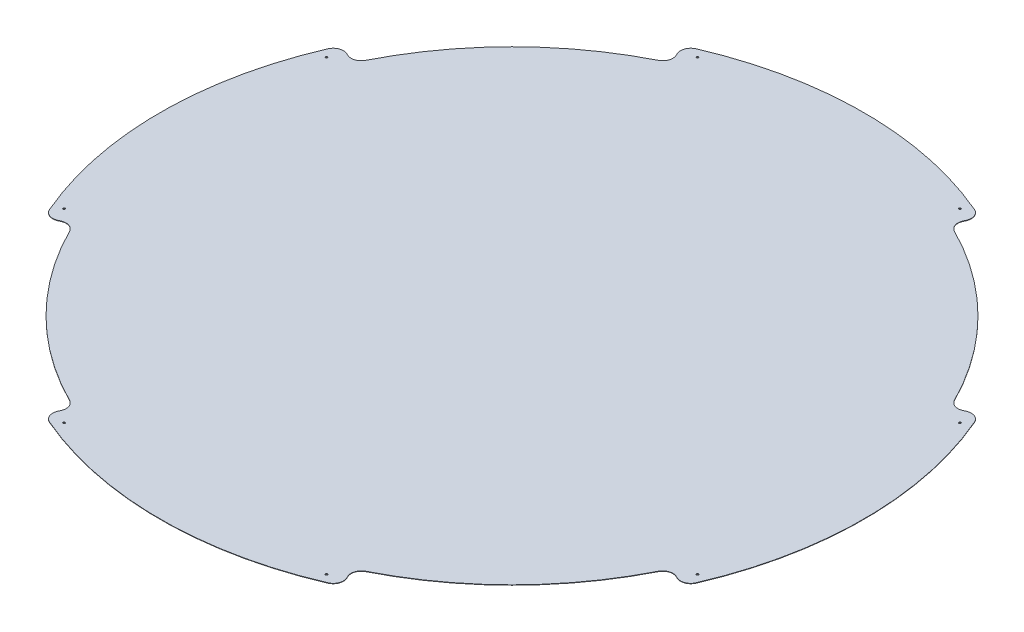
SolidWorks part; units mm, degrees
ref_plane "Front" through (0, 0, 0) normal (0, 0, 1) x (1, 0, 0)
ref_plane "Top" through (0, 0, 0) normal (0, 1, 0) x (1, 0, 0)
ref_plane "Right" through (0, 0, 0) normal (1, 0, 0) x (0, 0, -1)
sketch "Sketch1" plane through (0, 0, 0) normal (0, 1, 0) x (1, 0, 0)
  line L0 (0, 0) -> (0, 168) construction
  line L1 (0, 0) -> (64.2908, 155.2118) construction
  line L2 (0, 0) -> (155.2118, 64.2908) construction
  line L3 (0, 0) -> (155.2118, -64.2908) construction
  line L4 (0, 0) -> (64.2908, -155.2118) construction
  line L5 (0, 0) -> (-64.2908, -155.2118) construction
  line L6 (0, 0) -> (-155.2118, -64.2908) construction
  line L7 (0, 0) -> (-155.2118, 64.2908) construction
  line L8 (0, 0) -> (-64.2908, 155.2118) construction
  line L9 (70.757, 151.7389) -> (70.3342, 150.8322)
  line L10 (-70.757, 151.7389) -> (-70.3342, 150.8322)
  line L11 (151.7389, 70.757) -> (150.8322, 70.3342)
  line L12 (151.7389, -70.757) -> (150.8322, -70.3342)
  line L13 (70.757, -151.7389) -> (70.3342, -150.8322)
  line L14 (-70.757, -151.7389) -> (-70.3342, -150.8322)
  line L15 (-151.7389, -70.757) -> (-150.8322, -70.3342)
  line L16 (-151.7389, 70.757) -> (-150.8322, 70.3342)
  arc A0 (-72.6175, 144.2531) -> (-144.2531, 72.6175) centre (0, 0) ccw
  circle A1 centre (0, 0) radius 168 construction
  arc A2 (-158.4446, 68.2024) -> (-158.4446, -68.2024) centre (0, 0) ccw
  arc A3 (68.2024, 158.4446) -> (-68.2024, 158.4446) centre (0, 0) ccw
  arc A4 (144.2531, 72.6175) -> (72.6175, 144.2531) centre (0, 0) ccw
  arc A5 (158.4446, -68.2024) -> (158.4446, 68.2024) centre (0, 0) ccw
  arc A6 (72.6175, -144.2531) -> (144.2531, -72.6175) centre (0, 0) ccw
  arc A7 (-68.2024, -158.4446) -> (68.2024, -158.4446) centre (0, 0) ccw
  arc A8 (-144.2531, -72.6175) -> (-72.6175, -144.2531) centre (0, 0) ccw
  arc A9 (-151.7389, -70.757) -> (-158.4446, -68.2024) centre (-153.852, -66.2255) cw
  arc A10 (-150.8322, -70.3342) -> (-144.2531, -72.6175) centre (-148.7191, -74.8657) cw
  arc A11 (-70.757, -151.7389) -> (-68.2024, -158.4446) centre (-66.2255, -153.852) ccw
  arc A12 (-70.3342, -150.8322) -> (-72.6175, -144.2531) centre (-74.8657, -148.7191) ccw
  arc A13 (70.757, -151.7389) -> (68.2024, -158.4446) centre (66.2255, -153.852) cw
  arc A14 (70.3342, -150.8322) -> (72.6175, -144.2531) centre (74.8657, -148.7191) cw
  arc A15 (150.8322, -70.3342) -> (144.2531, -72.6175) centre (148.7191, -74.8657) ccw
  arc A16 (151.7389, -70.757) -> (158.4446, -68.2024) centre (153.852, -66.2255) ccw
  arc A17 (151.7389, 70.757) -> (158.4446, 68.2024) centre (153.852, 66.2255) cw
  arc A18 (150.8322, 70.3342) -> (144.2531, 72.6175) centre (148.7191, 74.8657) cw
  arc A19 (-150.8322, 70.3342) -> (-144.2531, 72.6175) centre (-148.7191, 74.8657) ccw
  arc A20 (-151.7389, 70.757) -> (-158.4446, 68.2024) centre (-153.852, 66.2255) ccw
  arc A21 (70.3342, 150.8322) -> (72.6175, 144.2531) centre (74.8657, 148.7191) ccw
  arc A22 (70.757, 151.7389) -> (68.2024, 158.4446) centre (66.2255, 153.852) ccw
  arc A23 (-70.3342, 150.8322) -> (-72.6175, 144.2531) centre (-74.8657, 148.7191) cw
  arc A24 (-70.757, 151.7389) -> (-68.2024, 158.4446) centre (-66.2255, 153.852) cw
  circle A25 centre (-64.2908, 155.2118) radius 0.5
  circle A26 centre (64.2908, 155.2118) radius 0.5
  circle A27 centre (155.2118, 64.2908) radius 0.5
  circle A28 centre (155.2118, -64.2908) radius 0.5
  circle A29 centre (64.2908, -155.2118) radius 0.5
  circle A30 centre (-64.2908, -155.2118) radius 0.5
  circle A31 centre (-155.2118, -64.2908) radius 0.5
  circle A32 centre (-155.2118, 64.2908) radius 0.5
  point P15 (0, 0)
  point P34 (0, 0)
  point P59 (72.9017, 156.3381)
  dimension "D1" = 323
  dimension "D5" = 345
  dimension "D9" = 5
  dimension "D10" = 1
  dimension "D2" = 168
  dimension "D3" = 22.5
  dimension "D6" = 25
  dimension "D7" = 25
  dimension "D4" = 8
  dimension "D8" = 4
extrude "Boss-Extrude1" add sketch "Sketch1" along normal blind 0.19
sketch "Sketch2" plane through (0, 0, 0) normal (0, 1, 0) x (1, 0, 0)
  line L8 (-151.7389, -70.757) -> (-150.8322, -70.3342)
  line L9 (-70.3342, -150.8322) -> (-70.757, -151.7389)
  line L10 (70.757, -151.7389) -> (70.3342, -150.8322)
  line L11 (150.8322, -70.3342) -> (151.7389, -70.757)
  line L12 (151.7389, 70.757) -> (150.8322, 70.3342)
  line L13 (70.3342, 150.8322) -> (70.757, 151.7389)
  line L14 (-70.757, 151.7389) -> (-70.3342, 150.8322)
  line L15 (-150.8322, 70.3342) -> (-151.7389, 70.757)
  line L16 (-151.7389, -70.757) -> (-150.8322, -70.3342)
  line L17 (-70.3342, -150.8322) -> (-70.757, -151.7389)
  line L18 (70.757, -151.7389) -> (70.3342, -150.8322)
  line L19 (150.8322, -70.3342) -> (151.7389, -70.757)
  line L20 (151.7389, 70.757) -> (150.8322, 70.3342)
  line L21 (70.3342, 150.8322) -> (70.757, 151.7389)
  line L22 (-70.757, 151.7389) -> (-70.3342, 150.8322)
  line L23 (-150.8322, 70.3342) -> (-151.7389, 70.757)
  circle A0 centre (-155.2118, 64.2908) radius 0.5 construction
  circle A1 centre (-155.2118, -64.2908) radius 0.5 construction
  circle A2 centre (64.2908, -155.2118) radius 0.5 construction
  circle A3 centre (-64.2908, -155.2118) radius 0.5 construction
  circle A4 centre (155.2118, -64.2908) radius 0.5 construction
  circle A5 centre (155.2118, 64.2908) radius 0.5 construction
  circle A6 centre (64.2908, 155.2118) radius 0.5 construction
  circle A7 centre (-64.2908, 155.2118) radius 0.5 construction
  circle A8 centre (-155.2118, 64.2908) radius 0.5
  circle A9 centre (-155.2118, -64.2908) radius 0.5
  circle A10 centre (64.2908, -155.2118) radius 0.5
  circle A11 centre (-64.2908, -155.2118) radius 0.5
  circle A12 centre (155.2118, -64.2908) radius 0.5
  circle A13 centre (155.2118, 64.2908) radius 0.5
  circle A14 centre (64.2908, 155.2118) radius 0.5
  circle A15 centre (-64.2908, 155.2118) radius 0.5
  arc A24 (-158.4446, -68.2024) -> (-151.7389, -70.757) centre (-153.852, -66.2255) ccw
  arc A25 (-144.2531, -72.6175) -> (-150.8322, -70.3342) centre (-148.7191, -74.8657) ccw
  arc A26 (-144.2531, -72.6175) -> (-72.6175, -144.2531) centre (0, 0) ccw
  arc A27 (-70.3342, -150.8322) -> (-72.6175, -144.2531) centre (-74.8657, -148.7191) ccw
  arc A28 (-70.757, -151.7389) -> (-68.2024, -158.4446) centre (-66.2255, -153.852) ccw
  arc A29 (-68.2024, -158.4446) -> (68.2024, -158.4446) centre (0, 0) ccw
  arc A30 (68.2024, -158.4446) -> (70.757, -151.7389) centre (66.2255, -153.852) ccw
  arc A31 (72.6175, -144.2531) -> (70.3342, -150.8322) centre (74.8657, -148.7191) ccw
  arc A32 (72.6175, -144.2531) -> (144.2531, -72.6175) centre (0, 0) ccw
  arc A33 (150.8322, -70.3342) -> (144.2531, -72.6175) centre (148.7191, -74.8657) ccw
  arc A34 (151.7389, -70.757) -> (158.4446, -68.2024) centre (153.852, -66.2255) ccw
  arc A35 (158.4446, -68.2024) -> (158.4446, 68.2024) centre (0, 0) ccw
  arc A36 (158.4446, 68.2024) -> (151.7389, 70.757) centre (153.852, 66.2255) ccw
  arc A37 (144.2531, 72.6175) -> (150.8322, 70.3342) centre (148.7191, 74.8657) ccw
  arc A38 (144.2531, 72.6175) -> (72.6175, 144.2531) centre (0, 0) ccw
  arc A39 (70.3342, 150.8322) -> (72.6175, 144.2531) centre (74.8657, 148.7191) ccw
  arc A40 (70.757, 151.7389) -> (68.2024, 158.4446) centre (66.2255, 153.852) ccw
  arc A41 (68.2024, 158.4446) -> (-68.2024, 158.4446) centre (0, 0) ccw
  arc A42 (-68.2024, 158.4446) -> (-70.757, 151.7389) centre (-66.2255, 153.852) ccw
  arc A43 (-72.6175, 144.2531) -> (-70.3342, 150.8322) centre (-74.8657, 148.7191) ccw
  arc A44 (-72.6175, 144.2531) -> (-144.2531, 72.6175) centre (0, 0) ccw
  arc A45 (-150.8322, 70.3342) -> (-144.2531, 72.6175) centre (-148.7191, 74.8657) ccw
  arc A46 (-151.7389, 70.757) -> (-158.4446, 68.2024) centre (-153.852, 66.2255) ccw
  arc A47 (-158.4446, 68.2024) -> (-158.4446, -68.2024) centre (0, 0) ccw
  arc A48 (-158.4446, -68.2024) -> (-151.7389, -70.757) centre (-153.852, -66.2255) ccw
  arc A49 (-144.2531, -72.6175) -> (-150.8322, -70.3342) centre (-148.7191, -74.8657) ccw
  arc A50 (-144.2531, -72.6175) -> (-72.6175, -144.2531) centre (0, 0) ccw
  arc A51 (-70.3342, -150.8322) -> (-72.6175, -144.2531) centre (-74.8657, -148.7191) ccw
  arc A52 (-70.757, -151.7389) -> (-68.2024, -158.4446) centre (-66.2255, -153.852) ccw
  arc A53 (-68.2024, -158.4446) -> (68.2024, -158.4446) centre (0, 0) ccw
  arc A54 (68.2024, -158.4446) -> (70.757, -151.7389) centre (66.2255, -153.852) ccw
  arc A55 (72.6175, -144.2531) -> (70.3342, -150.8322) centre (74.8657, -148.7191) ccw
  arc A56 (72.6175, -144.2531) -> (144.2531, -72.6175) centre (0, 0) ccw
  arc A57 (150.8322, -70.3342) -> (144.2531, -72.6175) centre (148.7191, -74.8657) ccw
  arc A58 (151.7389, -70.757) -> (158.4446, -68.2024) centre (153.852, -66.2255) ccw
  arc A59 (158.4446, -68.2024) -> (158.4446, 68.2024) centre (0, 0) ccw
  arc A60 (158.4446, 68.2024) -> (151.7389, 70.757) centre (153.852, 66.2255) ccw
  arc A61 (144.2531, 72.6175) -> (150.8322, 70.3342) centre (148.7191, 74.8657) ccw
  arc A62 (144.2531, 72.6175) -> (72.6175, 144.2531) centre (0, 0) ccw
  arc A63 (70.3342, 150.8322) -> (72.6175, 144.2531) centre (74.8657, 148.7191) ccw
  arc A64 (70.757, 151.7389) -> (68.2024, 158.4446) centre (66.2255, 153.852) ccw
  arc A65 (68.2024, 158.4446) -> (-68.2024, 158.4446) centre (0, 0) ccw
  arc A66 (-68.2024, 158.4446) -> (-70.757, 151.7389) centre (-66.2255, 153.852) ccw
  arc A67 (-72.6175, 144.2531) -> (-70.3342, 150.8322) centre (-74.8657, 148.7191) ccw
  arc A68 (-72.6175, 144.2531) -> (-144.2531, 72.6175) centre (0, 0) ccw
  arc A69 (-150.8322, 70.3342) -> (-144.2531, 72.6175) centre (-148.7191, 74.8657) ccw
  arc A70 (-151.7389, 70.757) -> (-158.4446, 68.2024) centre (-153.852, 66.2255) ccw
  arc A71 (-158.4446, 68.2024) -> (-158.4446, -68.2024) centre (0, 0) ccw
  dimension "D1" = 0
sketch "Sketch3" plane through (0, 0, 0) normal (0, 1, 0) x (1, 0, 0)
  line L8 (-151.7389, -70.757) -> (-150.8322, -70.3342)
  line L9 (-70.3342, -150.8322) -> (-70.757, -151.7389)
  line L10 (70.757, -151.7389) -> (70.3342, -150.8322)
  line L11 (150.8322, -70.3342) -> (151.7389, -70.757)
  line L12 (151.7389, 70.757) -> (150.8322, 70.3342)
  line L13 (70.3342, 150.8322) -> (70.757, 151.7389)
  line L14 (-70.757, 151.7389) -> (-70.3342, 150.8322)
  line L15 (-150.8322, 70.3342) -> (-151.7389, 70.757)
  line L16 (-151.7389, -70.757) -> (-150.8322, -70.3342)
  line L17 (-70.3342, -150.8322) -> (-70.757, -151.7389)
  line L18 (70.757, -151.7389) -> (70.3342, -150.8322)
  line L19 (150.8322, -70.3342) -> (151.7389, -70.757)
  line L20 (151.7389, 70.757) -> (150.8322, 70.3342)
  line L21 (70.3342, 150.8322) -> (70.757, 151.7389)
  line L22 (-70.757, 151.7389) -> (-70.3342, 150.8322)
  line L23 (-150.8322, 70.3342) -> (-151.7389, 70.757)
  circle A0 centre (-64.2908, 155.2118) radius 0.5 construction
  circle A1 centre (-64.2908, 155.2118) radius 0.5
  circle A2 centre (64.2908, 155.2118) radius 0.5 construction
  circle A3 centre (64.2908, 155.2118) radius 0.5
  circle A4 centre (155.2118, 64.2908) radius 0.5 construction
  circle A5 centre (155.2118, 64.2908) radius 0.5
  circle A6 centre (155.2118, -64.2908) radius 0.5 construction
  circle A7 centre (155.2118, -64.2908) radius 0.5
  circle A8 centre (64.2908, -155.2118) radius 0.5 construction
  circle A9 centre (64.2908, -155.2118) radius 0.5
  circle A10 centre (-64.2908, -155.2118) radius 0.5 construction
  circle A11 centre (-64.2908, -155.2118) radius 0.5
  circle A12 centre (-155.2118, -64.2908) radius 0.5 construction
  circle A13 centre (-155.2118, -64.2908) radius 0.5
  circle A14 centre (-155.2118, 64.2908) radius 0.5 construction
  circle A15 centre (-155.2118, 64.2908) radius 0.5
  arc A24 (-158.4446, -68.2024) -> (-151.7389, -70.757) centre (-153.852, -66.2255) ccw
  arc A25 (-144.2531, -72.6175) -> (-150.8322, -70.3342) centre (-148.7191, -74.8657) ccw
  arc A26 (-144.2531, -72.6175) -> (-72.6175, -144.2531) centre (0, 0) ccw
  arc A27 (-70.3342, -150.8322) -> (-72.6175, -144.2531) centre (-74.8657, -148.7191) ccw
  arc A28 (-70.757, -151.7389) -> (-68.2024, -158.4446) centre (-66.2255, -153.852) ccw
  arc A29 (-68.2024, -158.4446) -> (68.2024, -158.4446) centre (0, 0) ccw
  arc A30 (68.2024, -158.4446) -> (70.757, -151.7389) centre (66.2255, -153.852) ccw
  arc A31 (72.6175, -144.2531) -> (70.3342, -150.8322) centre (74.8657, -148.7191) ccw
  arc A32 (72.6175, -144.2531) -> (144.2531, -72.6175) centre (0, 0) ccw
  arc A33 (150.8322, -70.3342) -> (144.2531, -72.6175) centre (148.7191, -74.8657) ccw
  arc A34 (151.7389, -70.757) -> (158.4446, -68.2024) centre (153.852, -66.2255) ccw
  arc A35 (158.4446, -68.2024) -> (158.4446, 68.2024) centre (0, 0) ccw
  arc A36 (158.4446, 68.2024) -> (151.7389, 70.757) centre (153.852, 66.2255) ccw
  arc A37 (144.2531, 72.6175) -> (150.8322, 70.3342) centre (148.7191, 74.8657) ccw
  arc A38 (144.2531, 72.6175) -> (72.6175, 144.2531) centre (0, 0) ccw
  arc A39 (70.3342, 150.8322) -> (72.6175, 144.2531) centre (74.8657, 148.7191) ccw
  arc A40 (70.757, 151.7389) -> (68.2024, 158.4446) centre (66.2255, 153.852) ccw
  arc A41 (68.2024, 158.4446) -> (-68.2024, 158.4446) centre (0, 0) ccw
  arc A42 (-68.2024, 158.4446) -> (-70.757, 151.7389) centre (-66.2255, 153.852) ccw
  arc A43 (-72.6175, 144.2531) -> (-70.3342, 150.8322) centre (-74.8657, 148.7191) ccw
  arc A44 (-72.6175, 144.2531) -> (-144.2531, 72.6175) centre (0, 0) ccw
  arc A45 (-150.8322, 70.3342) -> (-144.2531, 72.6175) centre (-148.7191, 74.8657) ccw
  arc A46 (-151.7389, 70.757) -> (-158.4446, 68.2024) centre (-153.852, 66.2255) ccw
  arc A47 (-158.4446, 68.2024) -> (-158.4446, -68.2024) centre (0, 0) ccw
  arc A48 (-158.4446, -68.2024) -> (-151.7389, -70.757) centre (-153.852, -66.2255) ccw
  arc A49 (-144.2531, -72.6175) -> (-150.8322, -70.3342) centre (-148.7191, -74.8657) ccw
  arc A50 (-144.2531, -72.6175) -> (-72.6175, -144.2531) centre (0, 0) ccw
  arc A51 (-70.3342, -150.8322) -> (-72.6175, -144.2531) centre (-74.8657, -148.7191) ccw
  arc A52 (-70.757, -151.7389) -> (-68.2024, -158.4446) centre (-66.2255, -153.852) ccw
  arc A53 (-68.2024, -158.4446) -> (68.2024, -158.4446) centre (0, 0) ccw
  arc A54 (68.2024, -158.4446) -> (70.757, -151.7389) centre (66.2255, -153.852) ccw
  arc A55 (72.6175, -144.2531) -> (70.3342, -150.8322) centre (74.8657, -148.7191) ccw
  arc A56 (72.6175, -144.2531) -> (144.2531, -72.6175) centre (0, 0) ccw
  arc A57 (150.8322, -70.3342) -> (144.2531, -72.6175) centre (148.7191, -74.8657) ccw
  arc A58 (151.7389, -70.757) -> (158.4446, -68.2024) centre (153.852, -66.2255) ccw
  arc A59 (158.4446, -68.2024) -> (158.4446, 68.2024) centre (0, 0) ccw
  arc A60 (158.4446, 68.2024) -> (151.7389, 70.757) centre (153.852, 66.2255) ccw
  arc A61 (144.2531, 72.6175) -> (150.8322, 70.3342) centre (148.7191, 74.8657) ccw
  arc A62 (144.2531, 72.6175) -> (72.6175, 144.2531) centre (0, 0) ccw
  arc A63 (70.3342, 150.8322) -> (72.6175, 144.2531) centre (74.8657, 148.7191) ccw
  arc A64 (70.757, 151.7389) -> (68.2024, 158.4446) centre (66.2255, 153.852) ccw
  arc A65 (68.2024, 158.4446) -> (-68.2024, 158.4446) centre (0, 0) ccw
  arc A66 (-68.2024, 158.4446) -> (-70.757, 151.7389) centre (-66.2255, 153.852) ccw
  arc A67 (-72.6175, 144.2531) -> (-70.3342, 150.8322) centre (-74.8657, 148.7191) ccw
  arc A68 (-72.6175, 144.2531) -> (-144.2531, 72.6175) centre (0, 0) ccw
  arc A69 (-150.8322, 70.3342) -> (-144.2531, 72.6175) centre (-148.7191, 74.8657) ccw
  arc A70 (-151.7389, 70.757) -> (-158.4446, 68.2024) centre (-153.852, 66.2255) ccw
  arc A71 (-158.4446, 68.2024) -> (-158.4446, -68.2024) centre (0, 0) ccw
  dimension "D1" = 0
